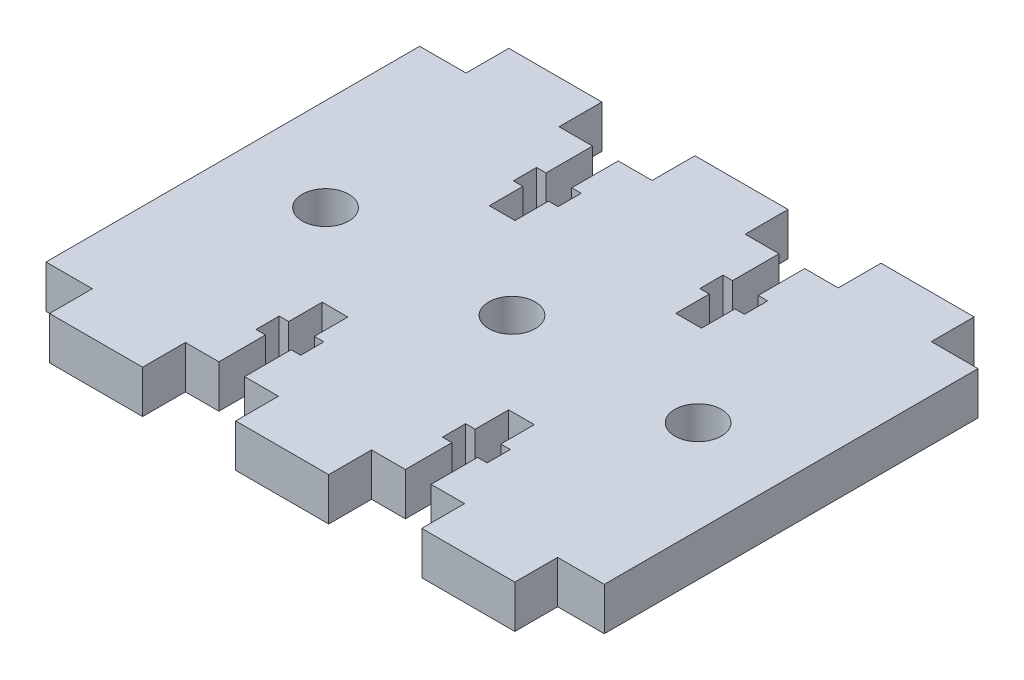
SolidWorks part; units mm, degrees
ref_plane "Front Plane" through (0, 0, 0) normal (0, 0, 1) x (1, 0, 0)
ref_plane "Top Plane" through (0, 0, 0) normal (0, 1, 0) x (1, 0, 0)
ref_plane "Right Plane" through (0, 0, 0) normal (1, 0, 0) x (0, 0, -1)
sketch "Sketch1" plane through (0, 0, 0) normal (0, 1, 0) x (1, 0, 0)
  line L0 (38.1, 0) -> (-38.1, 0) construction
  line L1 (38.1, -25.5) -> (31.7255, -25.5)
  line L2 (38.1, -25.5) -> (38.1, 25.5)
  line L3 (38.1, 25.5) -> (31.7255, 25.5)
  line L4 (-38.1, -25.5) -> (-38.1, 25.5)
  line L5 (38.1, -25.5) -> (-38.1, 25.5) construction
  line L6 (38.1, 25.5) -> (-38.1, -25.5) construction
  line L7 (-0.0245, 24.411) -> (-0.0245, -26.589) construction
  line L8 (-6.3745, 25.5) -> (-10.9963, 25.5)
  line L9 (6.3255, 31.342) -> (-6.3745, 31.342)
  line L10 (6.3255, 31.342) -> (6.3255, 25.5)
  line L11 (-31.7745, 25.5) -> (-38.1, 25.5)
  line L12 (-6.3745, 31.342) -> (-6.3745, 25.5)
  line L13 (6.3255, 31.342) -> (-6.3745, 25.5) construction
  line L14 (6.3255, 25.5) -> (-6.3745, 31.342) construction
  line L15 (31.7255, 31.342) -> (19.0255, 25.5) construction
  line L16 (-31.7745, 25.5) -> (-31.7745, 31.342)
  line L17 (-31.7745, 31.342) -> (-19.0745, 31.342)
  line L18 (-19.0745, 25.5) -> (-19.0745, 31.342)
  line L19 (-31.7745, 25.5) -> (-19.0745, 31.342) construction
  line L20 (-31.7745, 31.342) -> (-19.0745, 25.5) construction
  line L21 (31.7255, 25.5) -> (19.0255, 31.342) construction
  line L22 (19.0255, 25.5) -> (19.0255, 31.342)
  line L23 (31.7255, 31.342) -> (19.0255, 31.342)
  line L24 (31.7255, 25.5) -> (31.7255, 31.342)
  line L25 (19.0255, 25.5) -> (14.4526, 25.5)
  line L26 (-12.7489, 23.322) -> (-12.7489, 0) construction
  line L27 (12.7, 25.5) -> (12.7, -25.5) construction
  line L28 (-9.7009, 15.975) -> (-9.7009, 19.15)
  line L29 (-14.5015, 15.975) -> (-15.7969, 15.975)
  line L30 (-10.9963, 19.15) -> (-10.9963, 25.5)
  line L31 (10.9474, 15.975) -> (14.4526, 11.403) construction
  line L32 (-14.5015, 19.15) -> (-14.5015, 25.5)
  line L33 (-10.9963, 19.15) -> (-14.5015, 25.5) construction
  line L34 (-10.9963, 25.5) -> (-14.5015, 19.15) construction
  line L35 (-9.7009, 15.975) -> (-10.9963, 15.975)
  line L36 (-15.7969, 15.975) -> (-15.7969, 19.15)
  line L37 (-9.7009, 19.15) -> (-10.9963, 19.15)
  line L38 (-14.5015, 19.15) -> (-15.7969, 19.15)
  line L39 (-14.5015, 25.5) -> (-19.0745, 25.5)
  line L40 (10.9474, 11.403) -> (14.4526, 15.975) construction
  line L41 (-10.9963, 11.403) -> (-14.5015, 11.403)
  line L42 (-10.9963, 11.403) -> (-10.9963, 15.975)
  line L43 (10.9474, 25.5) -> (14.4526, 19.15) construction
  line L44 (-14.5015, 11.403) -> (-14.5015, 15.975)
  line L45 (-10.9963, 11.403) -> (-14.5015, 15.975) construction
  line L46 (-10.9963, 15.975) -> (-14.5015, 11.403) construction
  line L47 (10.9474, 19.15) -> (14.4526, 25.5) construction
  line L48 (14.4526, 11.403) -> (14.4526, 15.975)
  line L49 (10.9474, 11.403) -> (10.9474, 15.975)
  line L50 (10.9474, 11.403) -> (14.4526, 11.403)
  line L51 (14.4526, 19.15) -> (15.748, 19.15)
  line L52 (9.652, 19.15) -> (10.9474, 19.15)
  line L53 (15.748, 15.975) -> (15.748, 19.15)
  line L54 (9.652, 15.975) -> (10.9474, 15.975)
  line L55 (14.4526, 19.15) -> (14.4526, 25.5)
  line L56 (10.9474, 19.15) -> (10.9474, 25.5)
  line L57 (14.4526, 15.975) -> (15.748, 15.975)
  line L58 (9.652, 15.975) -> (9.652, 19.15)
  line L59 (10.9474, 25.5) -> (6.3255, 25.5)
  line L60 (10.9474, -19.15) -> (14.4526, -25.5) construction
  line L61 (10.9474, -25.5) -> (14.4526, -19.15) construction
  line L62 (10.9474, -11.403) -> (14.4526, -15.975) construction
  line L63 (10.9474, -15.975) -> (14.4526, -11.403) construction
  line L64 (9.652, -15.975) -> (9.652, -19.15)
  line L65 (14.4526, -15.975) -> (15.748, -15.975)
  line L66 (10.9474, -19.15) -> (10.9474, -25.5)
  line L67 (14.4526, -19.15) -> (14.4526, -25.5)
  line L68 (9.652, -15.975) -> (10.9474, -15.975)
  line L69 (15.748, -15.975) -> (15.748, -19.15)
  line L70 (9.652, -19.15) -> (10.9474, -19.15)
  line L71 (14.4526, -19.15) -> (15.748, -19.15)
  line L72 (10.9474, -11.403) -> (14.4526, -11.403)
  line L73 (10.9474, -11.403) -> (10.9474, -15.975)
  line L74 (14.4526, -11.403) -> (14.4526, -15.975)
  line L75 (-14.5015, -15.975) -> (-15.7969, -15.975)
  line L76 (-14.5015, -19.15) -> (-15.7969, -19.15)
  line L77 (-15.7969, -15.975) -> (-15.7969, -19.15)
  line L78 (-10.9963, -15.975) -> (-14.5015, -11.403) construction
  line L79 (-10.9963, -11.403) -> (-14.5015, -15.975) construction
  line L80 (-10.9963, -25.5) -> (-14.5015, -19.15) construction
  line L81 (-10.9963, -19.15) -> (-14.5015, -25.5) construction
  line L82 (-14.5015, -11.403) -> (-14.5015, -15.975)
  line L83 (-10.9963, -11.403) -> (-10.9963, -15.975)
  line L84 (-10.9963, -11.403) -> (-14.5015, -11.403)
  line L85 (-9.7009, -19.15) -> (-10.9963, -19.15)
  line L86 (-9.7009, -15.975) -> (-10.9963, -15.975)
  line L87 (-14.5015, -19.15) -> (-14.5015, -25.5)
  line L88 (-10.9963, -19.15) -> (-10.9963, -25.5)
  line L89 (-9.7009, -15.975) -> (-9.7009, -19.15)
  line L90 (-14.5015, -25.5) -> (-19.0745, -25.5)
  line L91 (10.9474, -25.5) -> (6.3255, -25.5)
  line L92 (-31.7745, -25.5) -> (-31.7745, -31.342)
  line L93 (-19.0745, -25.5) -> (-19.0745, -31.342)
  line L94 (-6.3745, -31.342) -> (-6.3745, -25.5)
  line L95 (6.3255, -31.342) -> (6.3255, -25.5)
  line L96 (19.0255, -25.5) -> (19.0255, -31.342)
  line L97 (31.7255, -25.5) -> (31.7255, -31.342)
  line L98 (31.7255, -31.342) -> (19.0255, -31.342)
  line L99 (-31.7745, -31.342) -> (-19.0745, -31.342)
  line L100 (6.3255, -31.342) -> (-6.3745, -31.342)
  line L101 (-31.7745, -25.5) -> (-38.1, -25.5)
  line L102 (-6.3745, -25.5) -> (-10.9963, -25.5)
  line L103 (19.0255, -25.5) -> (14.4526, -25.5)
  line L104 (-15.7969, 17.5625) -> (-9.7009, 17.5625) construction
  point P0 (0, 0)
  point P10 (-0.0245, 28.421)
  point P15 (-25.4245, 28.421)
  point P24 (25.3755, 28.421)
  point P29 (-12.7489, 22.325)
  point P34 (-12.7489, 11.661)
  point P39 (-12.7489, 13.689)
  point P56 (12.7, 13.689)
  point P57 (12.7, 11.661)
  point P58 (12.7, 22.325)
  point P68 (12.7, 0)
  point P72 (12.7, -22.325)
  point P73 (12.7, -11.661)
  point P74 (12.7, -13.689)
  point P87 (-12.7489, -13.689)
  point P88 (-12.7489, -11.661)
  point P89 (-12.7489, -22.325)
  point P102 (25.3755, -28.421)
  point P103 (-25.4245, -28.421)
  point P104 (-0.0245, -28.421)
  point P107 (-12.7489, 17.5625)
  dimension "D1" = 76.2
  dimension "D2" = 51
  dimension "D3" = 12.7
  dimension "D4" = 5.842
  dimension "D5" = 12.7
  dimension "D6" = 5.842
  dimension "D7" = 25.4
  dimension "D8" = 3.5052
  dimension "D9" = 6.35
  dimension "D10" = 6.096
  dimension "D11" = 3.175
  dimension "D12" = 4.572
extrude "Boss-Extrude1" add sketch "Sketch1" along normal blind 5.842
sketch "Sketch2" plane through (0, 5.842, 0) normal (0, 1, 0) x (1, 0, 0)
  line L0 (-38.1, 0) -> (38.1, 0) construction
  line L1 (-38.1, 25.5) -> (-38.1, -25.5) construction
  line L2 (38.1, -25.5) -> (38.1, 25.5) construction
  line L3 (-0.0245, 31.342) -> (-0.0245, -31.342) construction
  line L4 (6.3255, 31.342) -> (-6.3745, 31.342) construction
  line L5 (-6.3745, -31.342) -> (6.3255, -31.342) construction
  circle A0 centre (0, 0) radius 3.175
  circle A1 centre (25.4, 0) radius 3.175
  circle A2 centre (-25.4489, 0) radius 3.175
  dimension "D1" = 6.35
  dimension "D2" = 6.35
  dimension "D3" = 25.4
extrude "Cut-Extrude1" cut sketch "Sketch2" against normal through all
sketch "Sketch3" [suppressed] plane through (0, 5.842, 0) normal (0, 1, 0) x (1, 0, 0)
  line L0 (-38.1, 0) -> (38.1, 0) construction
  line L1 (-38.1, 25.5) -> (-38.1, -25.5) construction
  line L2 (38.1, -25.5) -> (38.1, 25.5) construction
  line L4 (-17.4625, -6.35) -> (-42.8625, -6.35)
  line L5 (-17.4625, -6.35) -> (-17.4625, 6.35)
  line L6 (-17.4625, 6.35) -> (-42.8625, 6.35)
  line L7 (-42.8625, -6.35) -> (-42.8625, 6.35)
  line L8 (-17.4625, -6.35) -> (-42.8625, 6.35) construction
  line L9 (-17.4625, 6.35) -> (-42.8625, -6.35) construction
  point P6 (-30.1625, 0)
  dimension "D1" = 12.7
  dimension "D2" = 25.4
  dimension "D3" = 7.9375
extrude "Cut-Extrude2" [suppressed] cut sketch "Sketch3" against normal through all
fillet "Fillet1" [suppressed] radius 0.7937
